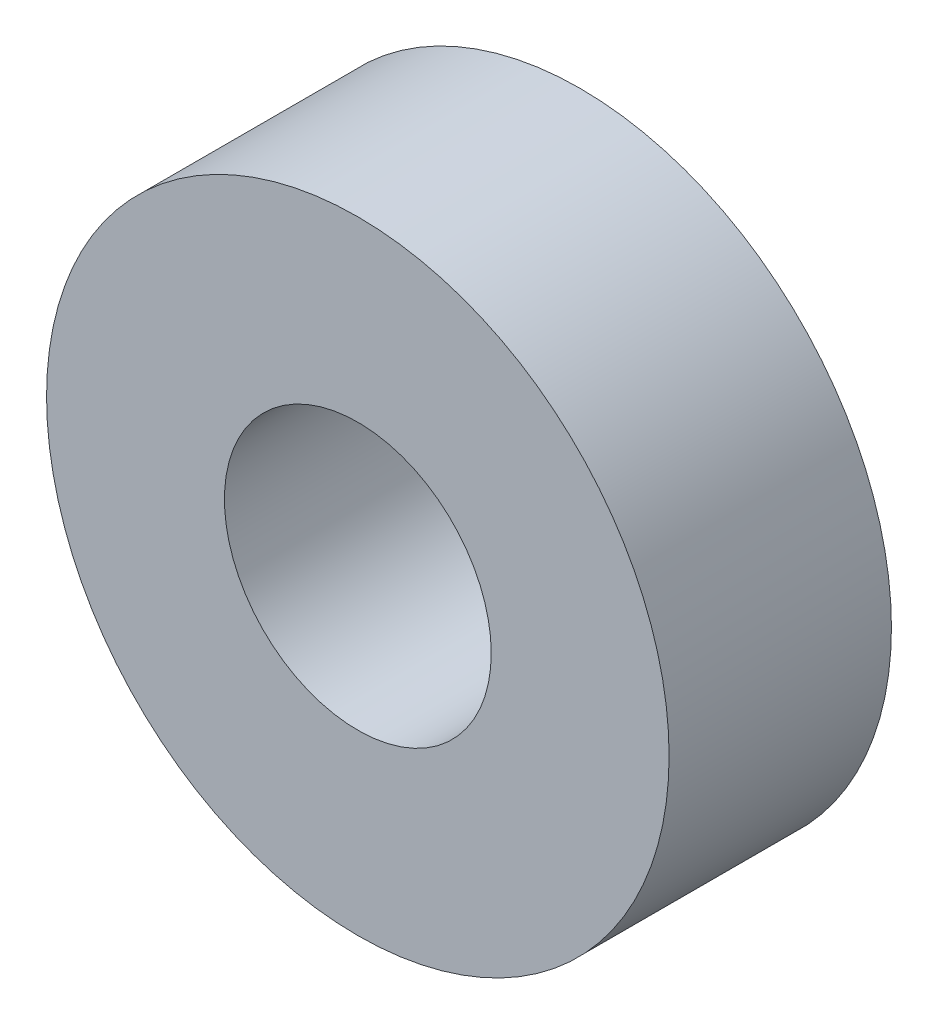
SolidWorks part; units mm, degrees
ref_plane "Plan de face" through (0, 0, 0) normal (0, 0, 1) x (1, 0, 0)
ref_plane "Plan de dessus" through (0, 0, 0) normal (0, 1, 0) x (1, 0, 0)
ref_plane "Plan de droite" through (0, 0, 0) normal (1, 0, 0) x (0, 0, -1)
sketch "Esquisse1" plane through (0, 0, 0) normal (0, 0, 1) x (1, 0, 0)
  circle A0 centre (0, 0) radius 7
  circle A1 centre (0, 0) radius 3
  dimension "D1" = 6
  dimension "D2" = 14
extrude "Boss.-Extru.1" add sketch "Esquisse1" along normal blind 5
